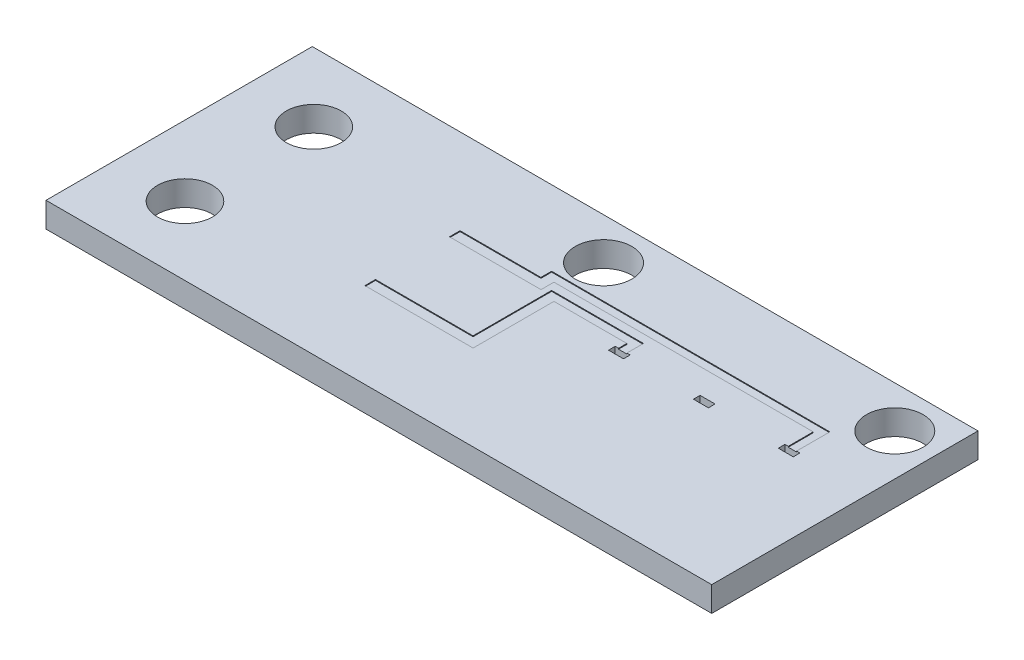
SolidWorks part; units mm, degrees
ref_plane "Front" through (0, 0, 0) normal (0, 0, 1) x (1, 0, 0)
ref_plane "Top" through (0, 0, 0) normal (0, 1, 0) x (1, 0, 0)
ref_plane "Right" through (0, 0, 0) normal (1, 0, 0) x (0, 0, -1)
sketch "Sketch1" plane through (0, 0, 0) normal (0, 1, 0) x (1, 0, 0)
  line L0 (-20, 0) -> (20, 0) construction
  line L1 (-20, 8) -> (20, 8)
  line L2 (-20, 8) -> (-20, -8)
  line L3 (-20, -8) -> (20, -8)
  line L4 (20, 8) -> (20, -8)
  line L5 (0, 8) -> (0, -8) construction
  dimension "D1" = 40
  dimension "D2" = 16
extrude "Boss-Extrude1" add sketch "Sketch1" along normal blind 1.5
sketch "Sketch2" plane through (0, 1.5, 0) normal (0, 1, 0) x (1, 0, 0)
  line L0 (-20, 5.5) -> (20, 5.5) construction
  line L1 (20, -8) -> (20, 8) construction
  circle A0 centre (0, 5.5) radius 1.7
  circle A1 centre (17.5, 5.5) radius 1.7
  dimension "D1" = 3.4
  dimension "D2" = 3.4
  dimension "D3" = 5.5
  dimension "D4" = 2.5
  dimension "D5" = 0
  dimension "D6" = 17.5
extrude "Cut-Extrude1" cut sketch "Sketch2" against normal through all
sketch "Sketch3" plane through (0, 1.5, 0) normal (0, 1, 0) x (1, 0, 0)
  line L0 (10.25, 1.5) -> (10.25, 1.1) construction
  line L1 (5.15, 1.5) -> (5.15, 1.1) construction
  line L2 (15.35, 1.5) -> (15.35, 1.1) construction
  line L3 (-20, -8) -> (20, -8) construction
  line L8 (14.9, 1.5) -> (14.9, 1.1)
  line L9 (4.7, 1.5) -> (5.6, 1.5)
  line L10 (4.7, 1.5) -> (4.7, 1.1)
  line L11 (4.7, 1.1) -> (5.6, 1.1)
  line L12 (5.6, 1.5) -> (5.6, 1.1)
  line L13 (9.8, 1.5) -> (10.7, 1.5)
  line L14 (9.8, 1.5) -> (9.8, 1.1)
  line L15 (9.8, 1.1) -> (10.7, 1.1)
  line L16 (10.7, 1.5) -> (10.7, 1.1)
  line L17 (15.8, 1.1) -> (14.9, 1.1)
  line L18 (15.8, 1.5) -> (15.8, 1.1)
  line L19 (15.8, 1.5) -> (14.9, 1.5)
  dimension "D1" = 10.25
  dimension "D2" = 5.1
  dimension "D3" = 9.1
  dimension "D4" = 0.9
  dimension "D5" = 0.4
extrude "Cut-Extrude2" cut sketch "Sketch3" against normal through all
sketch "Sketch5" plane through (0, 1.5, 0) normal (0, 1, 0) x (1, 0, 0)
  line L0 (-20, 8) -> (-20, -8) construction
  line L1 (-20, 0) -> (25.8774, 0) construction
  circle A0 centre (-15.78, 3.87) radius 1.65
  circle A1 centre (-15.78, -3.87) radius 1.65
  dimension "D3" = 3.3
  dimension "D1" = 4.22
  dimension "D2" = 7.74
extrude "Cut-Extrude4" cut sketch "Sketch5" against normal through all
sketch "Sketch6" plane through (0, 1.5, 0) normal (0, 1, 0) x (1, 0, 0)
  line L0 (4.9, 1.5) -> (4.9, 2)
  line L1 (4.9, 2) -> (0.5208, 2)
  line L2 (-5.9792, 2.8575) -> (-5.9792, 2.2225)
  line L3 (-5.9792, 2.2225) -> (-0.4792, 2.2225)
  line L4 (-0.1192, 2.5) -> (5.4, 2.5)
  line L5 (5.4, 2.5) -> (5.4, 1.5)
  line L6 (15.1, 1.5) -> (15.1, 3)
  line L7 (15.1, 3) -> (-0.4792, 3)
  line L8 (-0.4792, 2.2225) -> (-0.4792, 3)
  line L9 (-5.9792, 2.8575) -> (-1.1192, 2.8575)
  line L10 (-1.1192, 3.5) -> (15.6, 3.5)
  line L11 (15.6, 3.5) -> (15.6, 1.5)
  line L12 (-1.1192, 2.8575) -> (-1.1192, 3.5)
  line L13 (-5.9792, 2.2225) -> (-5.9792, 2.8575) construction
  line L14 (-5.9792, -2.8575) -> (-5.9792, -2.2225) construction
  line L15 (4.9, 1.5) -> (5.4, 1.5)
  line L16 (5.6, 1.5) -> (4.7, 1.5) construction
  line L17 (15.35, 1.5) -> (15.35, 2.4339) construction
  line L18 (5.15, 1.5) -> (5.15, 1.9747) construction
  line L21 (-3.8456, -2.2225) -> (-5.9792, -2.2225) construction
  line L22 (15.8, 1.5) -> (14.9, 1.5) construction
  line L23 (15.1, 1.5) -> (15.6, 1.5)
  line L26 (-3.8456, 2.8575) -> (-5.9792, 2.8575) construction
  line L27 (-5.9792, 2.2225) -> (-3.8456, 2.2225) construction
  line L28 (-5.9792, -2.2225) -> (-5.9792, -2.8575)
  line L29 (-5.9792, -2.8575) -> (0.5208, -2.8575)
  line L30 (0.5208, -2.8575) -> (0.5208, 2)
  line L31 (-0.1192, 2.5) -> (-0.1192, -2.2225)
  line L32 (-0.1192, -2.2225) -> (-5.9792, -2.2225)
  line L33 (-5.9792, -2.8575) -> (-3.8456, -2.8575) construction
  line L34 (0, 0) -> (-15.551, 0) construction
  dimension "D1" = 1
  dimension "D2" = 0.5
  dimension "D3" = 0.5
  dimension "D4" = 0.64
  dimension "D5" = 0.64
  dimension "D6" = 6.5
  dimension "D7" = 0.5
  dimension "D8" = 0.5
  dimension "D9" = 5.5
  dimension "D10" = 2
extrude "Cut-Extrude5" cut sketch "Sketch6" against normal blind 0.05
